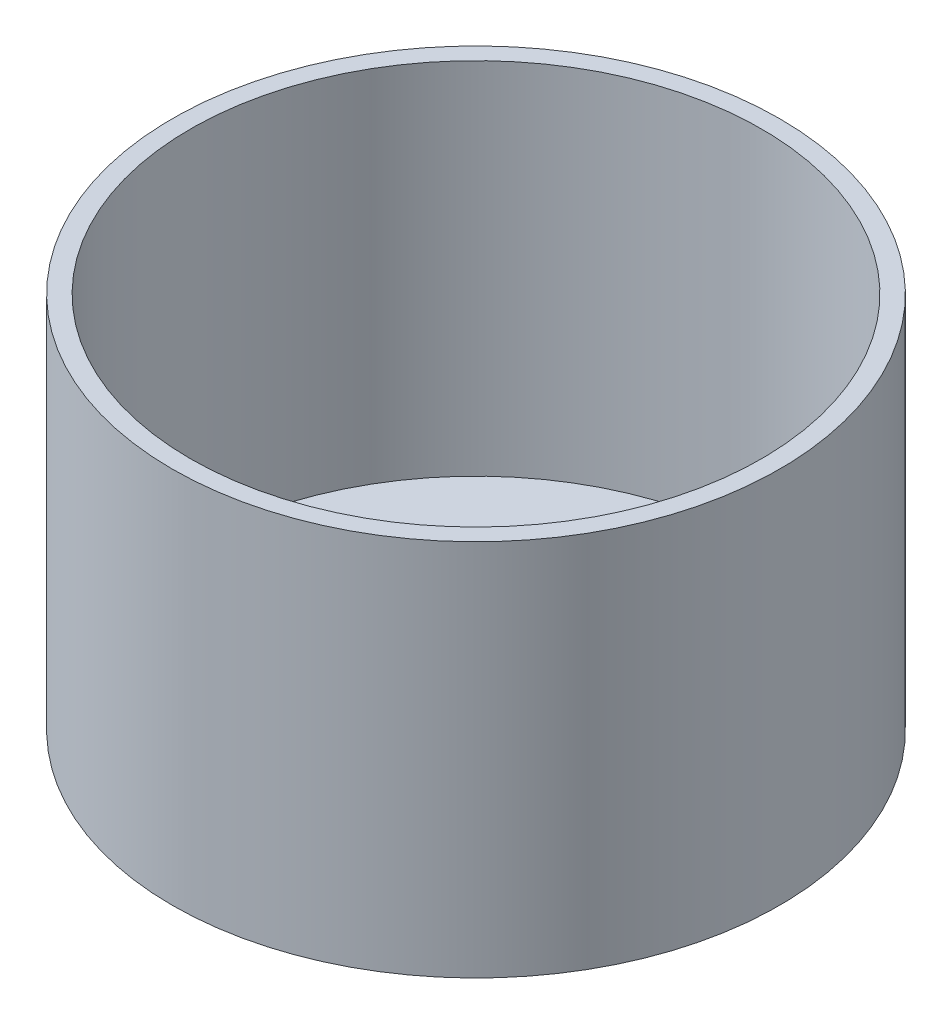
SolidWorks part; units mm, degrees
ref_plane "Front Plane" through (0, 0, 0) normal (0, 0, 1) x (1, 0, 0)
ref_plane "Top Plane" through (0, 0, 0) normal (0, 1, 0) x (1, 0, 0)
ref_plane "Right Plane" through (0, 0, 0) normal (1, 0, 0) x (0, 0, -1)
sketch "Sketch1" plane through (0, 0, 0) normal (0, 1, 0) x (1, 0, 0)
  circle A0 centre (0, 0) radius 31.75 construction
  circle A1 centre (0, 0) radius 33.75
  dimension "D1" = 2
  dimension "D2" = 63.5
extrude "Boss-Extrude1" add sketch "Sketch1" along normal blind 2
sketch "Sketch2" plane through (0, 2, 0) normal (0, 1, 0) x (1, 0, 0)
  circle A0 centre (0, 0) radius 31.75
  circle A1 centre (0, 0) radius 33.75
  circle A2 centre (0, 0) radius 33.75 construction
  circle A3 centre (0, 0) radius 31.75 construction
extrude "Boss-Extrude2" add sketch "Sketch2" along normal blind 40
